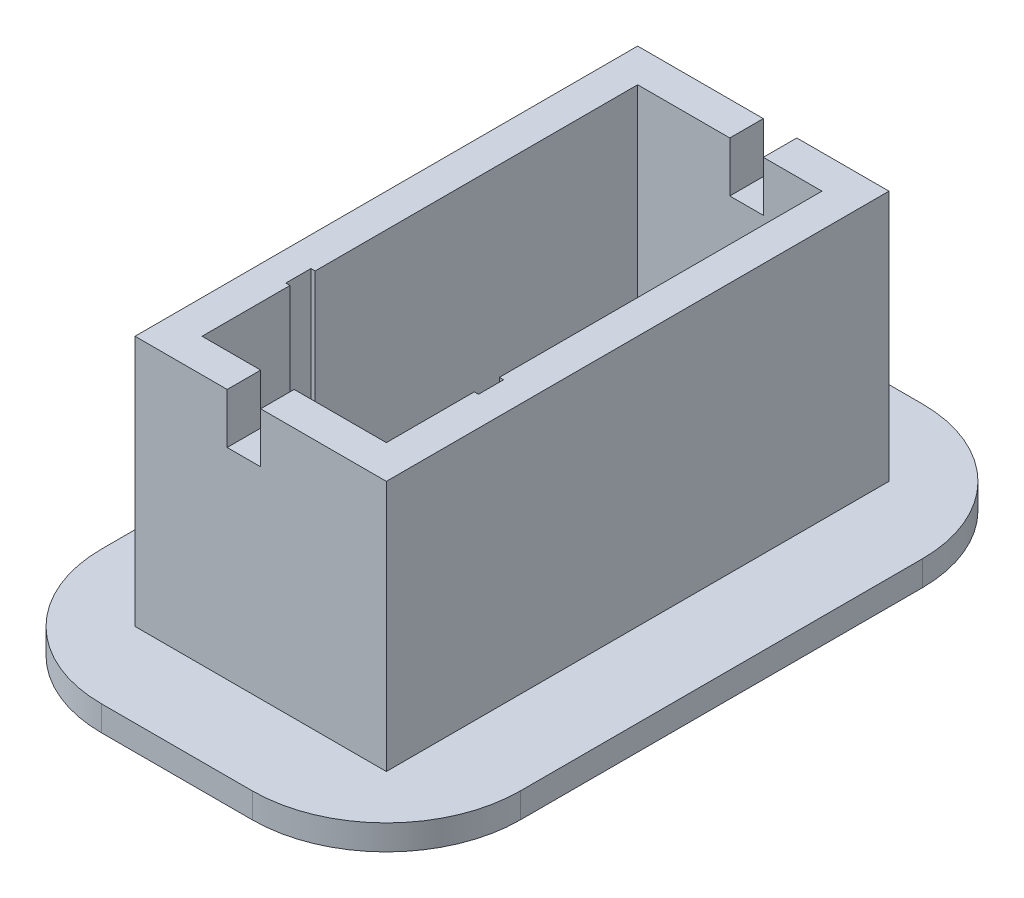
SolidWorks part; units mm, degrees
ref_plane "前视基准面" through (0, 0, 0) normal (0, 0, 1) x (1, 0, 0)
ref_plane "上视基准面" through (0, 0, 0) normal (0, 1, 0) x (1, 0, 0)
ref_plane "右视基准面" through (0, 0, 0) normal (1, 0, 0) x (0, 0, -1)
sketch "Sketch1" plane through (0, 0, 0) normal (0, 1, 0) x (1, 0, 0)
  line L0 (2, 2) -> (13, 2)
  line L1 (0, 0) -> (15, 0)
  line L2 (0, 0) -> (0, 30)
  line L3 (0, 30) -> (15, 30)
  line L4 (15, 0) -> (15, 30)
  line L5 (13, 2) -> (13, 7.25)
  line L6 (2, 28) -> (13, 28)
  line L7 (2, 2) -> (2, 7.25)
  line L8 (7.5, 2) -> (7.5, 8) construction
  line L9 (2, 8) -> (13, 8) construction
  line L10 (2, 8.75) -> (2, 28)
  line L11 (2, 8.75) -> (1.75, 8.75)
  line L12 (2, 2) -> (2, 28) construction
  line L13 (2, 7.25) -> (1.75, 7.25)
  line L14 (1.75, 8.75) -> (1.75, 7.25)
  line L15 (2, 8.75) -> (2, 7.25) construction
  line L16 (13, 7.25) -> (13.25, 7.25)
  line L17 (13.25, 8.75) -> (13.25, 7.25)
  line L18 (13, 8.75) -> (13.25, 8.75)
  line L19 (13, 8.75) -> (13, 28)
  line L20 (13, 2) -> (13, 28) construction
  line L21 (13, 8.75) -> (13, 7.25) construction
  dimension "D1" = 30
  dimension "D2" = 2
  dimension "D3" = 15
  dimension "D4" = 6
  dimension "D5" = 1.5
  dimension "D6" = 0.25
extrude "Boss-Extrude1" add sketch "Sketch1" along normal blind 15
sketch "Sketch2" plane through (0, 0, 0) normal (0, -1, 0) x (1, 0, 0)
  line L0 (-5, 5) -> (20, 5)
  line L1 (0, 0) -> (15, 0) construction
  line L2 (0, 0) -> (0, -30) construction
  line L3 (0, -30) -> (15, -30) construction
  line L4 (15, 0) -> (15, -30) construction
  line L5 (20, 5) -> (20, -35)
  line L6 (-5, -35) -> (20, -35)
  line L7 (-5, 5) -> (-5, -35)
  dimension "D1" = 5
extrude "Boss-Extrude2" add sketch "Sketch2" along normal blind 1.5
sketch "Sketch4" plane through (0, 15, 0) normal (0, 1, 0) x (1, 0, 0)
  line L0 (15, 30) -> (0, 30) construction
  line L1 (7.5, 30) -> (9.5, 30)
  line L2 (7.5, 30) -> (7.5, 28)
  line L3 (7.5, 28) -> (9.5, 28)
  line L4 (9.5, 30) -> (9.5, 28)
  line L5 (13, 28) -> (2, 28) construction
  line L6 (2, 2) -> (13, 2) construction
  line L7 (7.5, 2) -> (5.5, 2)
  line L8 (7.5, 2) -> (7.5, 0)
  line L9 (7.5, 0) -> (5.5, 0)
  line L10 (5.5, 2) -> (5.5, 0)
  line L11 (0, 0) -> (15, 0) construction
extrude "Cut-Extrude2" cut sketch "Sketch4" against normal blind 3
fillet "Fillet2" radius 8 4 edges at (20, -0.75, -35) (-5, -0.75, -35) (20, -0.75, 5) (-5, -0.75, 5)
